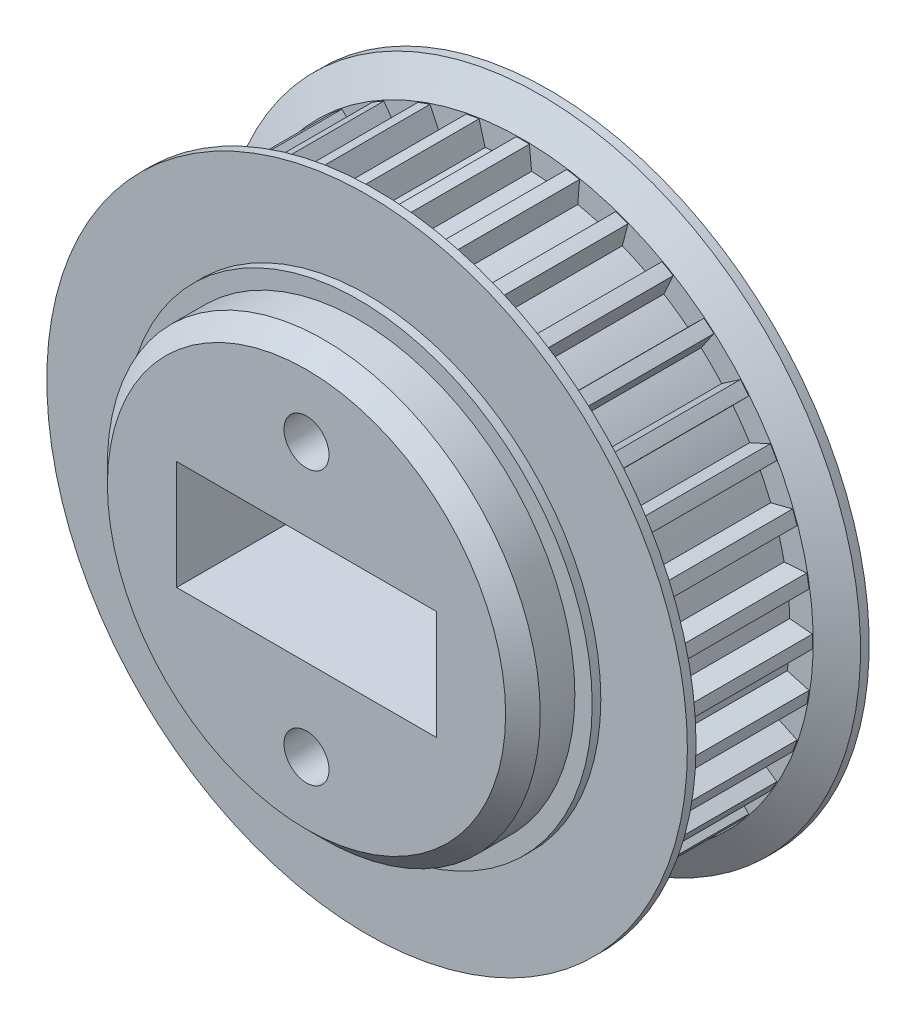
SolidWorks part; units mm, degrees
material "ABS"
ref_plane "Alzado" through (0, 0, 0) normal (0, 0, 1) x (1, 0, 0)
ref_plane "Planta" through (0, 0, 0) normal (0, 1, 0) x (1, 0, 0)
ref_plane "Vista lateral" through (0, 0, 0) normal (1, 0, 0) x (0, 0, -1)
sketch "Croquis1" plane through (0, 0, 0) normal (0, 0, 1) x (1, 0, 0)
  line L0 (0, 0) -> (0, 14.5885) construction
  line L1 (-0.375, 16.7142) -> (-0.5, 15.4103)
  line L2 (0.375, 16.7142) -> (0.5, 15.4103)
  line L3 (3.2717, 16.3952) -> (3.1684, 15.0894)
  line L4 (2.5331, 16.5254) -> (2.1836, 15.263)
  line L5 (6.069, 15.578) -> (5.7405, 14.3099)
  line L6 (5.3642, 15.8345) -> (4.8008, 14.652)
  line L7 (8.6819, 14.2874) -> (8.1382, 13.0957)
  line L8 (8.0323, 14.6624) -> (7.2721, 13.5957)
  line L9 (11.031, 12.5628) -> (10.2886, 11.4836)
  line L10 (10.4564, 13.0449) -> (9.5225, 12.1264)
  line L11 (13.0449, 10.4564) -> (12.1264, 9.5225)
  line L12 (12.5628, 11.031) -> (11.4836, 10.2886)
  line L13 (14.6624, 8.0323) -> (13.5957, 7.2721)
  line L14 (14.2874, 8.6819) -> (13.0957, 8.1382)
  line L15 (15.8345, 5.3642) -> (14.652, 4.8008)
  line L16 (15.578, 6.069) -> (14.3099, 5.7405)
  line L17 (16.5254, 2.5331) -> (15.263, 2.1836)
  line L18 (16.3952, 3.2717) -> (15.0894, 3.1684)
  line L19 (16.7142, -0.375) -> (15.4103, -0.5)
  line L20 (16.7142, 0.375) -> (15.4103, 0.5)
  line L21 (16.3952, -3.2717) -> (15.0894, -3.1684)
  line L22 (16.5254, -2.5331) -> (15.263, -2.1836)
  line L23 (15.578, -6.069) -> (14.3099, -5.7405)
  line L24 (15.8345, -5.3642) -> (14.652, -4.8008)
  line L25 (14.2874, -8.6819) -> (13.0957, -8.1382)
  line L26 (14.6624, -8.0323) -> (13.5957, -7.2721)
  line L27 (12.5628, -11.031) -> (11.4836, -10.2886)
  line L28 (13.0449, -10.4564) -> (12.1264, -9.5225)
  line L29 (10.4564, -13.0449) -> (9.5225, -12.1264)
  line L30 (11.031, -12.5628) -> (10.2886, -11.4836)
  line L31 (8.0323, -14.6624) -> (7.2721, -13.5957)
  line L32 (8.6819, -14.2874) -> (8.1382, -13.0957)
  line L33 (5.3642, -15.8345) -> (4.8008, -14.652)
  line L34 (6.069, -15.578) -> (5.7405, -14.3099)
  line L35 (2.5331, -16.5254) -> (2.1836, -15.263)
  line L36 (3.2717, -16.3952) -> (3.1684, -15.0894)
  line L37 (-0.375, -16.7142) -> (-0.5, -15.4103)
  line L38 (0.375, -16.7142) -> (0.5, -15.4103)
  line L39 (-3.2717, -16.3952) -> (-3.1684, -15.0894)
  line L40 (-2.5331, -16.5254) -> (-2.1836, -15.263)
  line L41 (-6.069, -15.578) -> (-5.7405, -14.3099)
  line L42 (-5.3642, -15.8345) -> (-4.8008, -14.652)
  line L43 (-8.6819, -14.2874) -> (-8.1382, -13.0957)
  line L44 (-8.0323, -14.6624) -> (-7.2721, -13.5957)
  line L45 (-11.031, -12.5628) -> (-10.2886, -11.4836)
  line L46 (-10.4564, -13.0449) -> (-9.5225, -12.1264)
  line L47 (-13.0449, -10.4564) -> (-12.1264, -9.5225)
  line L48 (-12.5628, -11.031) -> (-11.4836, -10.2886)
  line L49 (-14.6624, -8.0323) -> (-13.5957, -7.2721)
  line L50 (-14.2874, -8.6819) -> (-13.0957, -8.1382)
  line L51 (-15.8345, -5.3642) -> (-14.652, -4.8008)
  line L52 (-15.578, -6.069) -> (-14.3099, -5.7405)
  line L53 (-16.5254, -2.5331) -> (-15.263, -2.1836)
  line L54 (-16.3952, -3.2717) -> (-15.0894, -3.1684)
  line L55 (-16.7142, 0.375) -> (-15.4103, 0.5)
  line L56 (-16.7142, -0.375) -> (-15.4103, -0.5)
  line L57 (-16.3952, 3.2717) -> (-15.0894, 3.1684)
  line L58 (-16.5254, 2.5331) -> (-15.263, 2.1836)
  line L59 (-15.578, 6.069) -> (-14.3099, 5.7405)
  line L60 (-15.8345, 5.3642) -> (-14.652, 4.8008)
  line L61 (-14.2874, 8.6819) -> (-13.0957, 8.1382)
  line L62 (-14.6624, 8.0323) -> (-13.5957, 7.2721)
  line L63 (-12.5628, 11.031) -> (-11.4836, 10.2886)
  line L64 (-13.0449, 10.4564) -> (-12.1264, 9.5225)
  line L65 (-10.4564, 13.0449) -> (-9.5225, 12.1264)
  line L66 (-11.031, 12.5628) -> (-10.2886, 11.4836)
  line L67 (-8.0323, 14.6624) -> (-7.2721, 13.5957)
  line L68 (-8.6819, 14.2874) -> (-8.1382, 13.0957)
  line L69 (-5.3642, 15.8345) -> (-4.8008, 14.652)
  line L70 (-6.069, 15.578) -> (-5.7405, 14.3099)
  line L71 (-2.5331, 16.5254) -> (-2.1836, 15.263)
  line L72 (-3.2717, 16.3952) -> (-3.1684, 15.0894)
  arc A0 (-10.4564, 13.0449) -> (-11.031, 12.5628) centre (0, 0) ccw
  arc A1 (2.1836, 15.263) -> (0.5, 15.4103) centre (0, 0) ccw
  arc A2 (-12.5628, 11.031) -> (-13.0449, 10.4564) centre (0, 0) ccw
  arc A3 (-14.2874, 8.6819) -> (-14.6624, 8.0323) centre (0, 0) ccw
  arc A4 (-15.578, 6.069) -> (-15.8345, 5.3642) centre (0, 0) ccw
  arc A5 (-16.3952, 3.2717) -> (-16.5254, 2.5331) centre (0, 0) ccw
  arc A6 (-16.7142, 0.375) -> (-16.7142, -0.375) centre (0, 0) ccw
  arc A7 (-16.5254, -2.5331) -> (-16.3952, -3.2717) centre (0, 0) ccw
  arc A8 (-15.8345, -5.3642) -> (-15.578, -6.069) centre (0, 0) ccw
  arc A9 (-14.6624, -8.0323) -> (-14.2874, -8.6819) centre (0, 0) ccw
  arc A10 (-13.0449, -10.4564) -> (-12.5628, -11.031) centre (0, 0) ccw
  arc A11 (3.2717, 16.3952) -> (2.5331, 16.5254) centre (0, 0) ccw
  arc A12 (0.375, 16.7142) -> (-0.375, 16.7142) centre (0, 0) ccw
  arc A13 (-5.3642, 15.8345) -> (-6.069, 15.578) centre (0, 0) ccw
  arc A14 (-8.0323, 14.6624) -> (-8.6819, 14.2874) centre (0, 0) ccw
  arc A15 (-2.5331, 16.5254) -> (-3.2717, 16.3952) centre (0, 0) ccw
  arc A16 (6.069, 15.578) -> (5.3642, 15.8345) centre (0, 0) ccw
  arc A17 (8.6819, 14.2874) -> (8.0323, 14.6624) centre (0, 0) ccw
  arc A18 (11.031, 12.5628) -> (10.4564, 13.0449) centre (0, 0) ccw
  arc A19 (13.0449, 10.4564) -> (12.5628, 11.031) centre (0, 0) ccw
  arc A20 (14.6624, 8.0323) -> (14.2874, 8.6819) centre (0, 0) ccw
  arc A21 (15.8345, 5.3642) -> (15.578, 6.069) centre (0, 0) ccw
  arc A22 (16.5254, 2.5331) -> (16.3952, 3.2717) centre (0, 0) ccw
  arc A23 (16.7142, -0.375) -> (16.7142, 0.375) centre (0, 0) ccw
  arc A24 (16.3952, -3.2717) -> (16.5254, -2.5331) centre (0, 0) ccw
  arc A25 (15.578, -6.069) -> (15.8345, -5.3642) centre (0, 0) ccw
  arc A26 (8.0323, -14.6624) -> (8.6819, -14.2874) centre (0, 0) ccw
  arc A27 (5.3642, -15.8345) -> (6.069, -15.578) centre (0, 0) ccw
  arc A28 (2.5331, -16.5254) -> (3.2717, -16.3952) centre (0, 0) ccw
  arc A29 (-3.2717, -16.3952) -> (-2.5331, -16.5254) centre (0, 0) ccw
  arc A30 (-6.069, -15.578) -> (-5.3642, -15.8345) centre (0, 0) ccw
  arc A31 (-8.6819, -14.2874) -> (-8.0323, -14.6624) centre (0, 0) ccw
  arc A32 (-11.031, -12.5628) -> (-10.4564, -13.0449) centre (0, 0) ccw
  arc A33 (10.4564, -13.0449) -> (11.031, -12.5628) centre (0, 0) ccw
  arc A34 (12.5628, -11.031) -> (13.0449, -10.4564) centre (0, 0) ccw
  arc A35 (14.2874, -8.6819) -> (14.6624, -8.0323) centre (0, 0) ccw
  arc A36 (4.8008, 14.652) -> (3.1684, 15.0894) centre (0, 0) ccw
  arc A37 (7.2721, 13.5957) -> (5.7405, 14.3099) centre (0, 0) ccw
  arc A38 (-3.1684, 15.0894) -> (-4.8008, 14.652) centre (0, 0) ccw
  arc A39 (-0.5, 15.4103) -> (-2.1836, 15.263) centre (0, 0) ccw
  arc A40 (-5.7405, 14.3099) -> (-7.2721, 13.5957) centre (0, 0) ccw
  arc A41 (-8.1382, 13.0957) -> (-9.5225, 12.1264) centre (0, 0) ccw
  arc A42 (-10.2886, 11.4836) -> (-11.4836, 10.2886) centre (0, 0) ccw
  arc A43 (9.5225, 12.1264) -> (8.1382, 13.0957) centre (0, 0) ccw
  arc A44 (11.4836, 10.2886) -> (10.2886, 11.4836) centre (0, 0) ccw
  arc A45 (13.0957, 8.1382) -> (12.1264, 9.5225) centre (0, 0) ccw
  arc A46 (14.3099, 5.7405) -> (13.5957, 7.2721) centre (0, 0) ccw
  arc A47 (15.0894, 3.1684) -> (14.652, 4.8008) centre (0, 0) ccw
  arc A48 (15.4103, 0.5) -> (15.263, 2.1836) centre (0, 0) ccw
  arc A49 (15.263, -2.1836) -> (15.4103, -0.5) centre (0, 0) ccw
  arc A50 (14.652, -4.8008) -> (15.0894, -3.1684) centre (0, 0) ccw
  arc A51 (13.5957, -7.2721) -> (14.3099, -5.7405) centre (0, 0) ccw
  arc A52 (12.1264, -9.5225) -> (13.0957, -8.1382) centre (0, 0) ccw
  arc A53 (10.2886, -11.4836) -> (11.4836, -10.2886) centre (0, 0) ccw
  arc A54 (8.1382, -13.0957) -> (9.5225, -12.1264) centre (0, 0) ccw
  arc A55 (5.7405, -14.3099) -> (7.2721, -13.5957) centre (0, 0) ccw
  arc A56 (3.1684, -15.0894) -> (4.8008, -14.652) centre (0, 0) ccw
  arc A57 (0.5, -15.4103) -> (2.1836, -15.263) centre (0, 0) ccw
  arc A58 (-2.1836, -15.263) -> (-0.5, -15.4103) centre (0, 0) ccw
  arc A59 (-4.8008, -14.652) -> (-3.1684, -15.0894) centre (0, 0) ccw
  arc A60 (-7.2721, -13.5957) -> (-5.7405, -14.3099) centre (0, 0) ccw
  arc A61 (-9.5225, -12.1264) -> (-8.1382, -13.0957) centre (0, 0) ccw
  arc A62 (-11.4836, -10.2886) -> (-10.2886, -11.4836) centre (0, 0) ccw
  arc A63 (-13.0957, -8.1382) -> (-12.1264, -9.5225) centre (0, 0) ccw
  arc A64 (-14.3099, -5.7405) -> (-13.5957, -7.2721) centre (0, 0) ccw
  arc A65 (-15.0894, -3.1684) -> (-14.652, -4.8008) centre (0, 0) ccw
  arc A66 (-15.4103, -0.5) -> (-15.263, -2.1836) centre (0, 0) ccw
  arc A67 (-15.263, 2.1836) -> (-15.4103, 0.5) centre (0, 0) ccw
  arc A68 (-14.652, 4.8008) -> (-15.0894, 3.1684) centre (0, 0) ccw
  arc A69 (-13.5957, 7.2721) -> (-14.3099, 5.7405) centre (0, 0) ccw
  arc A70 (-12.1264, 9.5225) -> (-13.0957, 8.1382) centre (0, 0) ccw
  arc A71 (-0.375, -16.7142) -> (0.375, -16.7142) centre (0, 0) ccw
  circle A72 centre (0, 0) radius 2
  point P151 (0, 0)
  dimension "D1" = 1.3
  dimension "D6" = 4
  dimension "D2" = 1
  dimension "D3" = 0.75
  dimension "D5" = 1.69
  dimension "D4" = 36
extrude "Saliente-Extruir1" add sketch "Croquis1" along normal blind 7.5
sketch "Croquis2" plane through (0, 0, 7.5) normal (0, 0, 1) x (1, 0, 0)
  circle A0 centre (0, 0) radius 18.5
  circle A1 centre (0, 0) radius 2
  circle A2 centre (0, 0) radius 2 construction
  dimension "D1" = 37
extrude "Saliente-Extruir2" add sketch "Croquis2" along normal blind 1.5
sketch "Croquis3" plane through (0, 0, 9) normal (0, 0, 1) x (1, 0, 0)
  circle A0 centre (0, 0) radius 2
  circle A1 centre (0, 0) radius 12.5
  circle A3 centre (0, 0) radius 2 construction
  dimension "D1" = 25
sketch "Croquis4" plane through (0, 0, 0) normal (0, 0, -1) x (-1, 0, 0)
  circle A0 centre (0, 0) radius 2
  circle A1 centre (0, 0) radius 7.5
  circle A2 centre (0, 0) radius 2 construction
  dimension "D1" = 15
extrude "Saliente-Extruir4" add sketch "Croquis4" along normal blind 6
sketch "Croquis6" plane through (0, 0, 0) normal (0, 0, -1) x (-1, 0, 0)
  circle A0 centre (0, 0) radius 18.5
  circle A1 centre (0, 0) radius 2
  circle A2 centre (0, 0) radius 2 construction
  dimension "D1" = 37
extrude "Saliente-Extruir6" add sketch "Croquis6" along normal blind 1.5
sketch "Croquis5" plane through (0, 0, -1.5) normal (0, 0, -1) x (-1, 0, 0)
  circle A0 centre (0, 0) radius 2
  circle A1 centre (0, 0) radius 13.5
  circle A2 centre (0, 0) radius 2 construction
  dimension "D1" = 27
extrude "Saliente-Extruir5" add sketch "Croquis5" along normal blind 0.5
chamfer "Chaflán2" distance 1 angle 60 2 edges at (-18.5, 0, 0) (18.5, 0, 7.5)
extrude "Saliente-Extruir7" add sketch "Croquis3" along normal blind 3.5
chamfer "Chaflán4" distance 1 angle 45 2 edges at (-7.5, 0, -6) (12.5, 0, 12.5)
sketch "Croquis7" plane through (0, 0, 9) normal (0, 0, 1) x (1, 0, 0)
  circle A0 centre (0, 0) radius 2
  circle A1 centre (0, 0) radius 13.5
  circle A2 centre (0, 0) radius 2 construction
  dimension "D1" = 27
extrude "Saliente-Extruir8" add sketch "Croquis7" along normal blind 0.5
sketch "Croquis8" plane through (0, 0, 0) normal (0, 0, 1) x (1, 0, 0)
  line L0 (0, 0) -> (6.706, 0) construction
  line L1 (-7.5, 3.15) -> (7.5, 3.15)
  line L2 (-7.5, 3.15) -> (-7.5, -3.15)
  line L3 (-7.5, -3.15) -> (7.5, -3.15)
  line L4 (7.5, 3.15) -> (7.5, -3.15)
  line L5 (-7.5, 3.15) -> (7.5, -3.15) construction
  line L6 (-7.5, -3.15) -> (7.5, 3.15) construction
  circle A0 centre (0, 7.8756) radius 1.3
  circle A1 centre (0, -7.8756) radius 1.3
  point P0 (0, 0)
  dimension "D1" = 2.6
  dimension "D2" = 6.3
  dimension "D3" = 15
extrude "Cortar-Extruir1" cut sketch "Croquis8" along normal blind 27
sketch "Croquis9" plane through (0, 0, 12.5) normal (0, 0, 1) x (1, 0, 0)
  circle A0 centre (0, 7.8756) radius 1.3
  circle A1 centre (0, -7.8756) radius 1.3
  circle A2 centre (0, 7.8756) radius 1.3 construction
extrude "Cortar-Extruir2" cut sketch "Croquis9" against normal through all
